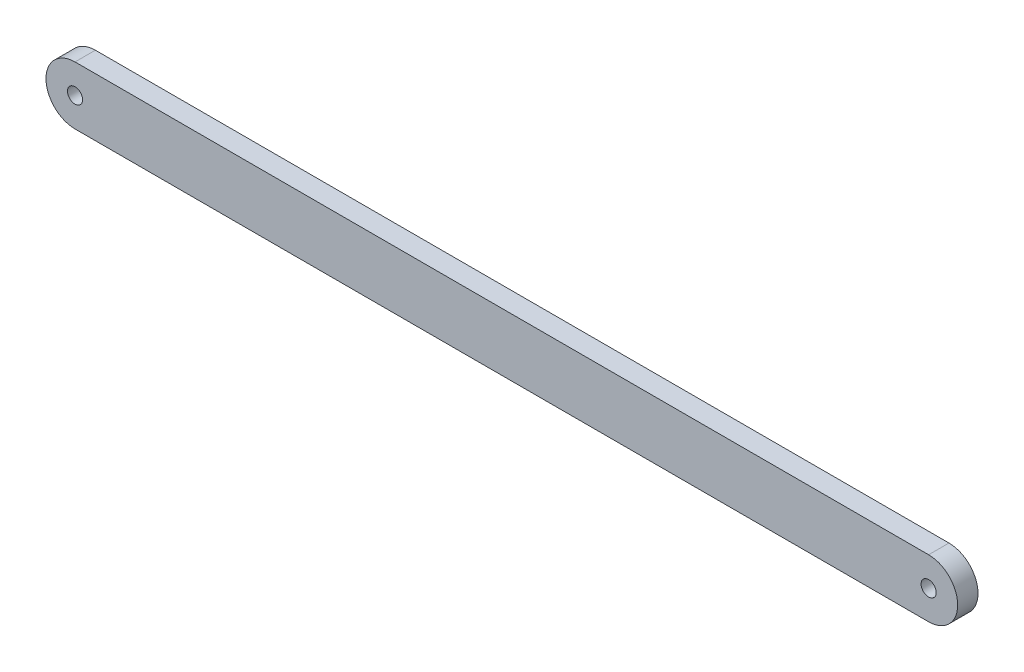
SolidWorks part; units mm, degrees
ref_plane "前视基准面" through (0, 0, 0) normal (0, 0, 1) x (1, 0, 0)
ref_plane "上视基准面" through (0, 0, 0) normal (0, 1, 0) x (1, 0, 0)
ref_plane "右视基准面" through (0, 0, 0) normal (1, 0, 0) x (0, 0, -1)
other "Configuration Table"
sketch "草图1" plane through (0, 0, 0) normal (0, 0, 1) x (1, 0, 0)
  line L0 (0, 0) -> (293.96, 0) construction
  line L1 (0, 10) -> (293.96, 10)
  line L2 (0, -10) -> (293.96, -10)
  arc A0 (0, 10) -> (0, -10) centre (0, 0) ccw
  arc A1 (293.96, -10) -> (293.96, 10) centre (293.96, 0) ccw
  circle A2 centre (0, 0) radius 2.6
  circle A3 centre (293.96, 0) radius 2.6
  point P3 (146.98, 0)
  dimension "D2" = 10
  dimension "D3" = 5.2
  dimension "D4" = 5.2
  dimension "D1" = 293.96
extrude "凸台-拉伸1" add sketch "草图1" along normal blind 7
